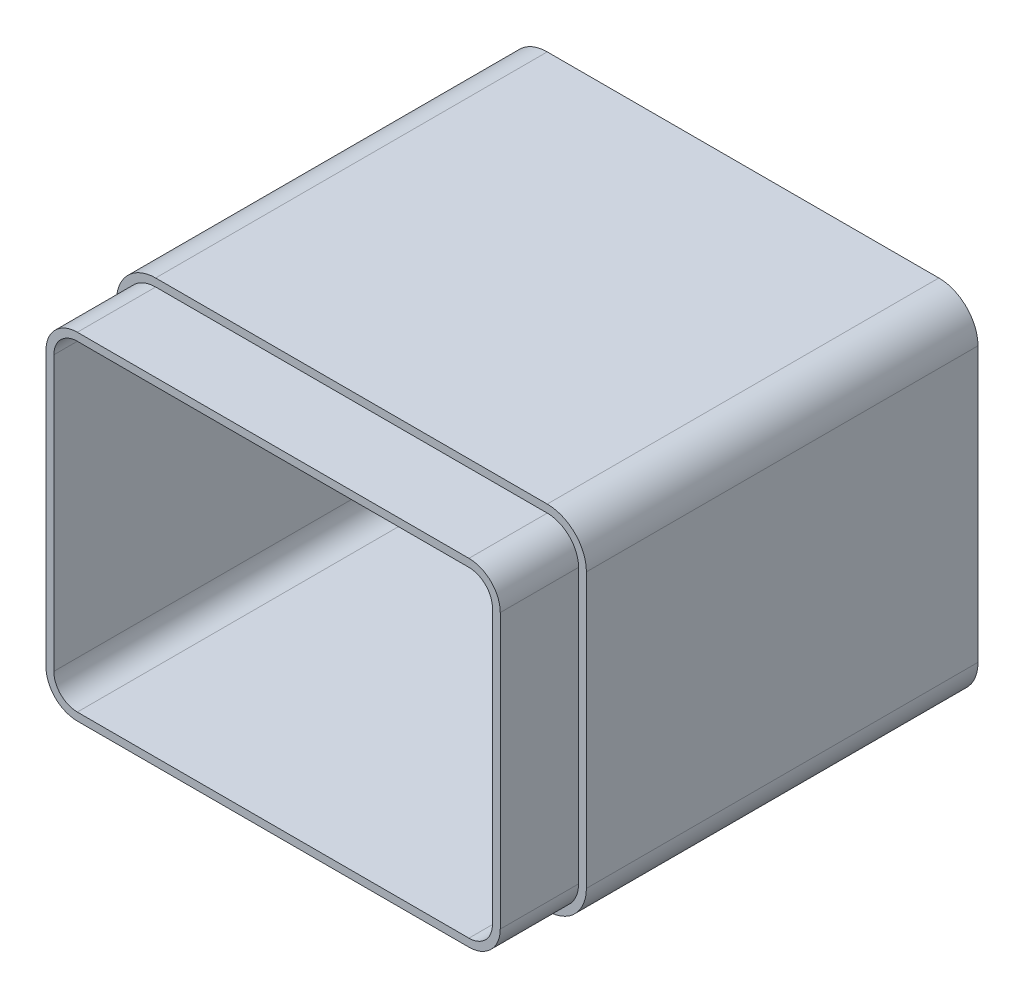
SolidWorks part; units mm, degrees
ref_plane "Front Plane" through (0, 0, 0) normal (0, 0, 1) x (1, 0, 0)
ref_plane "Top Plane" through (0, 0, 0) normal (0, 1, 0) x (1, 0, 0)
ref_plane "Right Plane" through (0, 0, 0) normal (1, 0, 0) x (0, 0, -1)
sketch "Sketch2" plane through (0, 0, 0) normal (0, 1, 0) x (1, 0, 0)
  line L1 (0, 0) -> (3048, 0)
  line L2 (0, 0) -> (0, 3048)
  line L3 (0, 3048) -> (3048, 3048)
  line L4 (3048, 0) -> (3048, 3048)
  dimension "D1" = 3048
  dimension "D2" = 3048
extrude "Boss-Extrude1" add sketch "Sketch2" along normal blind 2286
fillet "Fillet1" radius 254 4 edges at (3048, 0, -1524) (0, 2286, -1524) (0, 0, -1524) (3048, 2286, -1524)
shell "Shell1" thickness 101.6
sketch "Sketch4" plane through (0, 0, 0) normal (0, 0, 1) x (1, 0, 0)
  line L4 (3048, 254) -> (3048, 2032)
  line L5 (2794, 2286) -> (254, 2286)
  line L6 (0, 2032) -> (0, 254)
  line L7 (254, 0) -> (2794, 0)
  line L8 (3048, 254) -> (3048, 2032)
  line L9 (2794, 2286) -> (254, 2286)
  line L10 (0, 2032) -> (0, 254)
  line L11 (254, 0) -> (2794, 0)
  line L20 (2997.2, 254) -> (2997.2, 2032)
  line L21 (2794, 2235.2) -> (254, 2235.2)
  line L22 (50.8, 2032) -> (50.8, 254)
  line L23 (254, 50.8) -> (2794, 50.8)
  line L24 (2997.2, 254) -> (2997.2, 2032)
  line L25 (2794, 2235.2) -> (254, 2235.2)
  line L26 (50.8, 2032) -> (50.8, 254)
  line L27 (254, 50.8) -> (2794, 50.8)
  arc A4 (3048, 2032) -> (2794, 2286) centre (2794, 2032) ccw
  arc A5 (254, 2286) -> (0, 2032) centre (254, 2032) ccw
  arc A6 (0, 254) -> (254, 0) centre (254, 254) ccw
  arc A7 (2794, 0) -> (3048, 254) centre (2794, 254) ccw
  arc A8 (3048, 2032) -> (2794, 2286) centre (2794, 2032) ccw
  arc A9 (254, 2286) -> (0, 2032) centre (254, 2032) ccw
  arc A10 (0, 254) -> (254, 0) centre (254, 254) ccw
  arc A11 (2794, 0) -> (3048, 254) centre (2794, 254) ccw
  arc A20 (2997.2, 2032) -> (2794, 2235.2) centre (2794, 2032) ccw
  arc A21 (254, 2235.2) -> (50.8, 2032) centre (254, 2032) ccw
  arc A22 (50.8, 254) -> (254, 50.8) centre (254, 254) ccw
  arc A23 (2794, 50.8) -> (2997.2, 254) centre (2794, 254) ccw
  arc A24 (2997.2, 2032) -> (2794, 2235.2) centre (2794, 2032) ccw
  arc A25 (254, 2235.2) -> (50.8, 2032) centre (254, 2032) ccw
  arc A26 (50.8, 254) -> (254, 50.8) centre (254, 254) ccw
  arc A27 (2794, 50.8) -> (2997.2, 254) centre (2794, 254) ccw
  dimension "D1" = 0
  dimension "D2" = 50.8
extrude "Cut-Extrude1" cut sketch "Sketch4" against normal blind 508
